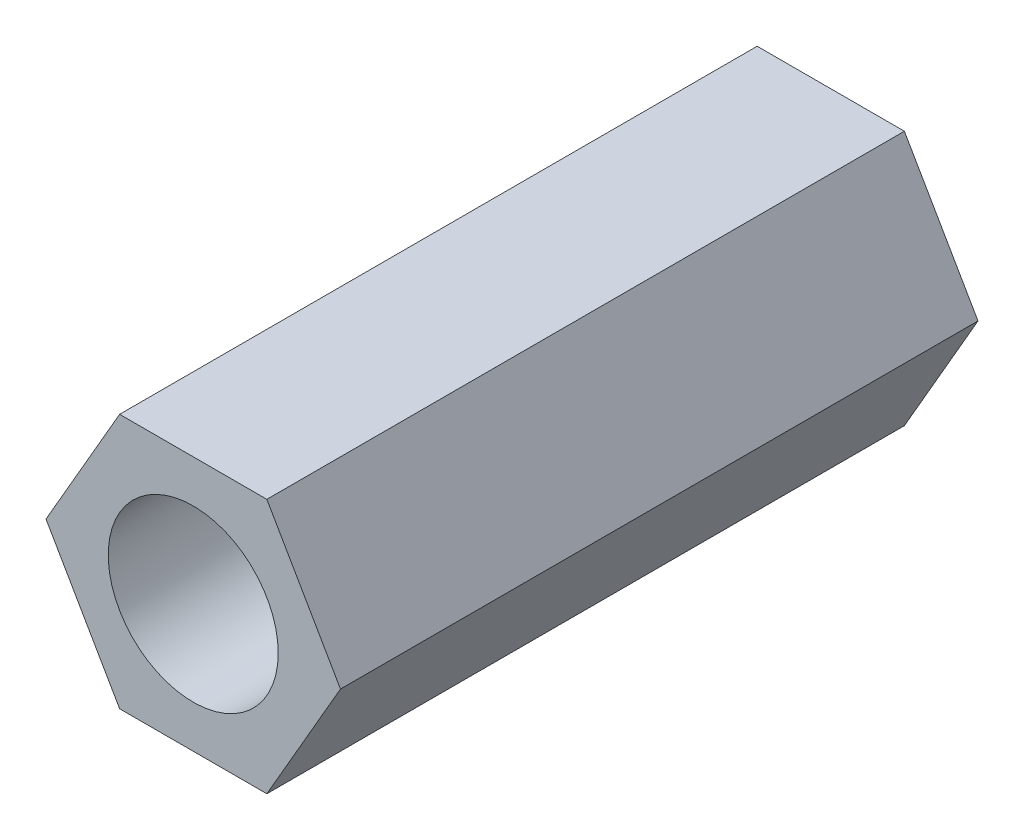
SolidWorks part; units mm, degrees
ref_plane "Plan de face" through (0, 0, 0) normal (0, 0, 1) x (1, 0, 0)
ref_plane "Plan de dessus" through (0, 0, 0) normal (0, 1, 0) x (1, 0, 0)
ref_plane "Plan de droite" through (0, 0, 0) normal (1, 0, 0) x (0, 0, -1)
sketch "Esquisse1" plane through (0, 0, 0) normal (0, 0, 1) x (1, 0, 0)
  line L1 (-3.4641, 0) -> (-1.7321, -3)
  line L2 (-1.7321, -3) -> (1.7321, -3)
  line L3 (1.7321, -3) -> (3.4641, 0)
  line L4 (3.4641, 0) -> (1.7321, 3)
  line L5 (1.7321, 3) -> (-1.7321, 3)
  line L6 (-1.7321, 3) -> (-3.4641, 0)
  circle A0 centre (0, 0) radius 2
  circle A1 centre (0, 0) radius 3 construction
  dimension "D1" = 4
  dimension "D2" = 6
extrude "Boss.-Extru.1" add sketch "Esquisse1" along normal blind 15
